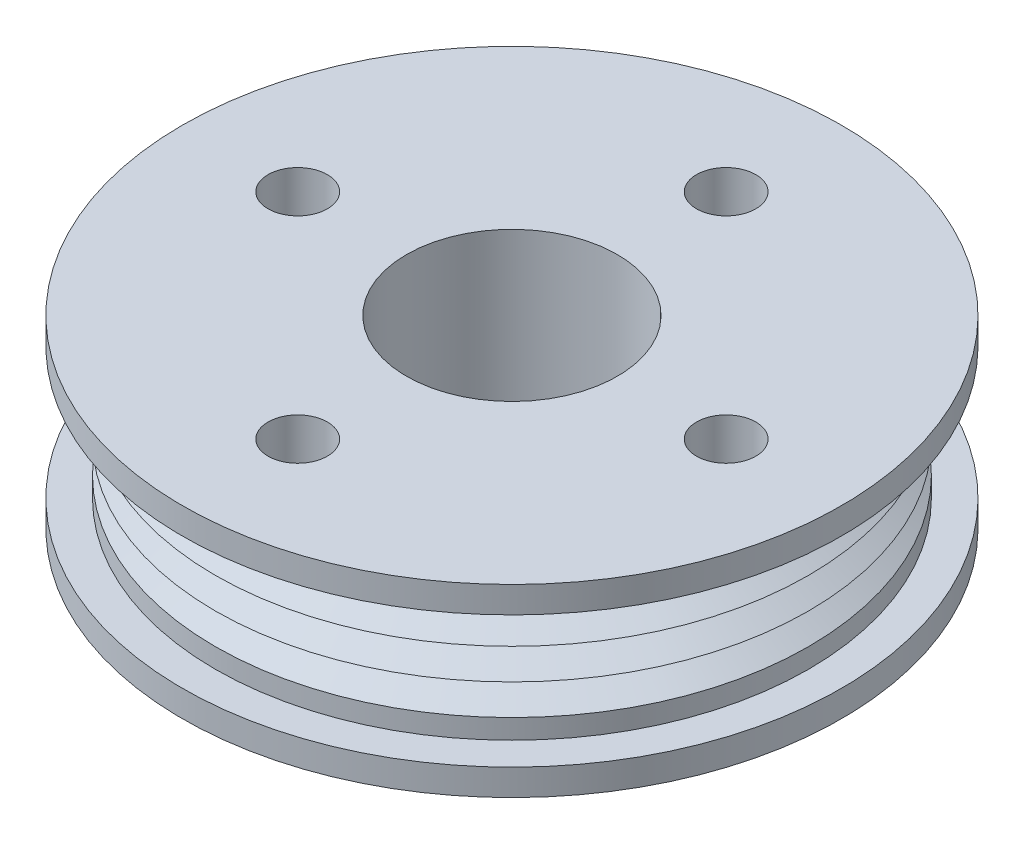
SolidWorks part; units mm, degrees
ref_plane "Plano frontal" through (0, 0, 0) normal (0, 0, 1) x (1, 0, 0)
ref_plane "Plano superior" through (0, 0, 0) normal (0, 1, 0) x (1, 0, 0)
ref_plane "Plano direito" through (0, 0, 0) normal (1, 0, 0) x (0, 0, -1)
sketch "Esboço1" plane through (0, 0, 0) normal (0, 0, 1) x (1, 0, 0)
  line L0 (0, 7) -> (0, -7)
  line L1 (0, -7) -> (-25, -7)
  line L2 (0, 7) -> (-25, 7)
  line L4 (-25, 7) -> (-25, 5)
  line L5 (-25, -7) -> (-25, -5)
  line L6 (-22.5, 5) -> (-22.5, 3.51)
  line L7 (-22.5, -5) -> (-25, -5)
  line L8 (-25, 5) -> (-22.5, 5)
  line L10 (-22.5, -3.51) -> (-22.5, -5)
  line L11 (-22.5, -3.51) -> (-20.7, -2.34)
  line L12 (-22.5, -1.17) -> (-20.7, -2.34)
  line L17 (-22.5, -1.17) -> (-20.7, 0)
  line L18 (-22.5, 1.17) -> (-20.7, 0)
  line L19 (-22.5, 1.17) -> (-20.7, 2.34)
  line L20 (-22.5, 3.51) -> (-20.7, 2.34)
  point P0 (-22.5, -1.17)
  point P4 (0, 0)
  point P5 (0, 0)
  dimension "D2" = 22.5
  dimension "D3" = 25
  dimension "D4" = 14
  dimension "D5" = 25
  dimension "D6" = 7.02
  dimension "D7" = 2.5
  dimension "D8" = 2.34
  dimension "D9" = 1.17
  dimension "D10" = 1.8
  dimension "D11" = 2.5
  dimension "D12" = 2
  dimension "D13" = 2
  dimension "D14" = 1.17
  dimension "D15" = 1.17
  dimension "D16" = 3.49
  dimension "D17" = 1.17
  dimension "D18" = 20.7
  dimension "D19" = 2.34
revolve "Revolução1" add sketch "Esboço1" angle 360 about L0
sketch "Esboço2" plane through (0, 7, 0) normal (0, 1, 0) x (1, 0, 0)
  circle A0 centre (16.25, 0) radius 2.25
  circle A1 centre (0, -16.25) radius 2.25
  circle A2 centre (-16.25, 0) radius 2.25
  circle A3 centre (0, 16.25) radius 2.25
  circle A4 centre (0, 0) radius 8
  point P12 (0, 0)
  dimension "D2" = 4.5
  dimension "D3" = 16
  dimension "D4" = 16.25
  dimension "D1" = 4
extrude "Corte-extrusão1" cut sketch "Esboço2" against normal blind 14
